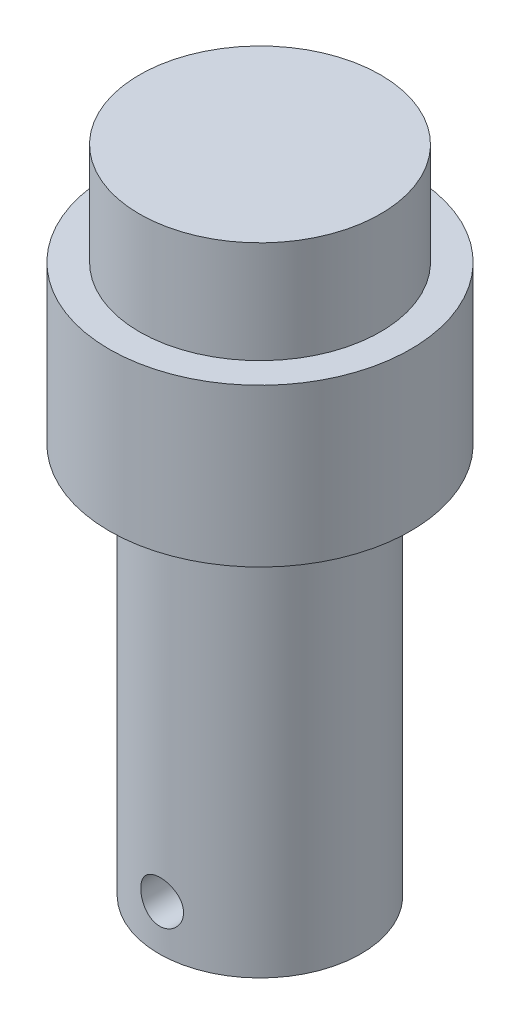
SolidWorks part; units mm, degrees
material "Alloy Steel (SS)"
ref_plane "Front Plane" through (0, 0, 0) normal (0, 0, 1) x (1, 0, 0)
ref_plane "Top Plane" through (0, 0, 0) normal (0, 1, 0) x (1, 0, 0)
ref_plane "Right Plane" through (0, 0, 0) normal (1, 0, 0) x (0, 0, -1)
sketch "Sketch1" plane through (0, 0, 0) normal (0, 1, 0) x (1, 0, 0)
  circle A0 centre (0, 0) radius 7.5565
  dimension "D1" = 15.113
extrude "Boss-Extrude1" add sketch "Sketch1" along normal blind 29.2608
sketch "Sketch2" plane through (0, 29.2608, 0) normal (0, 1, 0) x (1, 0, 0)
  circle A0 centre (0, 0) radius 11.2776
  dimension "D1" = 22.5552
extrude "Boss-Extrude2" add sketch "Sketch2" along normal blind 11.7805
sketch "Sketch3" plane through (0, 41.0413, 0) normal (0, 1, 0) x (1, 0, 0)
  circle A0 centre (0, 0) radius 9.0221
  dimension "D1" = 18.0442
extrude "Boss-Extrude3" add sketch "Sketch3" along normal blind 7.6352
sketch "Sketch4" plane through (0, 0, 0) normal (0, 0, 1) x (1, 0, 0)
  line L0 (7.5565, 0) -> (7.5565, 29.2608) construction
  circle A0 centre (0.066, 3.403) radius 1.5875
  dimension "D1" = 3.175
  dimension "D2" = 3.4036
  dimension "D3" = 7.4905
extrude "Cut-Extrude1" cut sketch "Sketch4" against normal through all both and the other way through all
